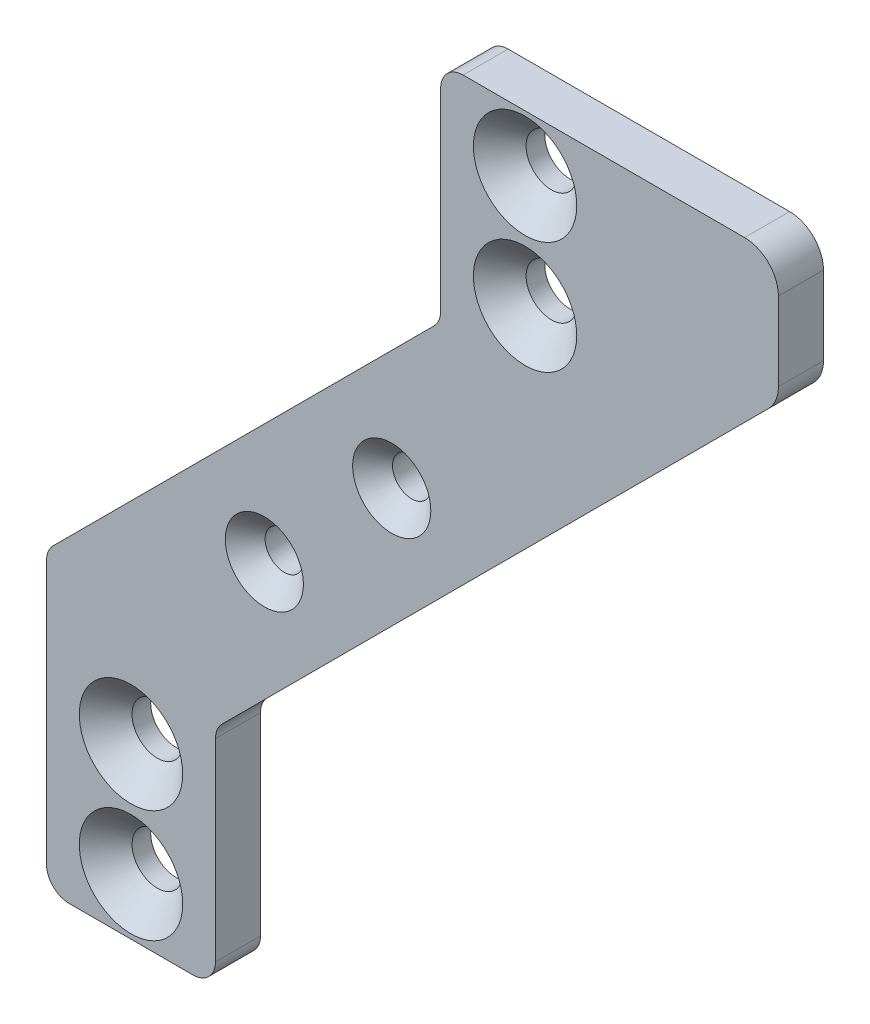
SolidWorks part; units mm, degrees
material "Thornel Mat VMA"
ref_plane "前视基准面" through (0, 0, 0) normal (0, 0, 1) x (1, 0, 0)
ref_plane "上视基准面" through (0, 0, 0) normal (0, 1, 0) x (1, 0, 0)
ref_plane "右视基准面" through (0, 0, 0) normal (1, 0, 0) x (0, 0, -1)
sketch "草图1" plane through (0, 0, 0) normal (0, 0, 1) x (1, 0, 0)
  line L0 (0, 0) -> (-15, 0)
  line L1 (-15, 0) -> (-15, 26.2132)
  line L2 (-15, 26.2132) -> (20, 61.2132)
  line L3 (20, 61.2132) -> (20, 81.2132)
  line L4 (20, 81.2132) -> (35, 81.2132)
  line L5 (35, 81.2132) -> (35, 55)
  line L6 (35, 55) -> (0, 20)
  line L7 (0, 20) -> (0, 0)
  line L8 (-95, 88.5038) -> (-95, -84.3524) construction
  line L9 (-7.5, 15) -> (-7.5, 0) construction
  line L10 (27.5, 81.2132) -> (27.5, 55.9789) construction
  circle A0 centre (-7.5, 15) radius 2 construction
  circle A1 centre (-7.5, 5) radius 2 construction
  circle A2 centre (27.5, 76.2132) radius 2 construction
  circle A3 centre (27.5, 66.2132) radius 2 construction
  point P23 (27.5, 66.2132)
  point P24 (27.5, 76.2132)
  point P25 (-7.5, 15)
  dimension "D7" = 4
  dimension "D8" = 4
  dimension "D9" = 10
  dimension "D10" = 5
  dimension "D13" = 4
  dimension "D14" = 4
  dimension "D15" = 10
  dimension "D16" = 5
  dimension "D1" = 260
  dimension "D2" = 190
  dimension "D3" = 45
  dimension "D4" = 15
  dimension "D5" = 15
  dimension "D6" = 15
  dimension "D11" = 20
  dimension "D12" = 20
extrude "凸台-拉伸1" add sketch "草图1" along normal blind 4
fillet "圆角1" radius 2 8 edges at (0, 0, 2) (-15, 0, 2) (-15, 26.2132, 2) (20, 61.2132, 2) (20, 81.2132, 2) (35, 55, 2) (0, 20, 2) (35, 81.2132, 2)
hole_wizard "M4 六角凹锥坑头螺钉的锥形沉头孔1" positions "3D草图2" profile "草图3" countersink size "M4" standard "DIN"
sketch3d "3D草图2"
  point P0 (27.5, 76.2132, 4)
  point P2 (27.5, 66.2132, 4)
  point P4 (-7.5, 15, 4)
  point P6 (-7.5, 5, 4)
sketch "草图3" plane through (27.5, 76.2132, 4) normal (1, 0, 0) x (0, -1, 0)
  line L0 (0, 0) -> (0, 25.8519)
  line L1 (0, 25.8519) -> (2.25, 24.5)
  line L2 (2.25, 24.5) -> (2.25, 2.34)
  line L3 (2.25, 2.34) -> (4.59, 0)
  line L5 (4.59, 0) -> (0, 0)
  line L6 (-2.25, 2.34) -> (-4.59, 0) construction
  line L10 (0, 25.8519) -> (-2.25, 24.5) construction
  line L11 (0, -6.35) -> (0, 107.95) construction
  dimension "孔直径" = 4.5
  dimension "孔深度" = 24.5
  dimension "近端锥形沉头孔直径" = 9.18
  dimension "近端锥形沉头孔角度" = 90
  dimension "导头角度" = 118
sketch "草图4" plane through (0, 0, 4) normal (0, 0, 1) x (1, 0, 0)
  line L0 (-4.7175, 25.8891) -> (24.7175, 55.3241) construction
  line L1 (19.4142, 60.6274) -> (-14.4142, 26.799) construction
  line L2 (0.5858, 20.5858) -> (-10.0208, 31.1924) construction
  line L3 (19.4142, 60.6274) -> (30.0208, 50.0208) construction
  line L4 (0.5858, 20.5858) -> (34.4142, 54.4142) construction
  point P4 (10, 40.6066)
  point P5 (4.3431, 34.9497)
  point P6 (24.7175, 55.3241)
  point P15 (15.6569, 46.2635)
  dimension "D2" = 8
  dimension "D1" = 8
hole_wizard "M3 六角凹锥坑头螺钉的锥形沉头孔1" positions "3D草图3" profile "草图5" countersink size "M3" standard "DIN"
sketch3d "3D草图3"
  point P0 (4.3431, 34.9497, 4)
  point P4 (15.6569, 46.2635, 4)
sketch "草图5" plane through (4.3431, 34.9497, 4) normal (1, 0, 0) x (0, -1, 0)
  line L0 (0, 0) -> (0, 25.5215)
  line L1 (0, 25.5215) -> (1.7, 24.5)
  line L2 (1.7, 24.5) -> (1.7, 1.77)
  line L3 (1.7, 1.77) -> (3.47, 0)
  line L5 (3.47, 0) -> (0, 0)
  line L6 (-1.7, 1.77) -> (-3.47, 0) construction
  line L10 (0, 25.5215) -> (-1.7, 24.5) construction
  line L11 (0, -6.35) -> (0, 107.95) construction
  dimension "孔直径" = 3.4
  dimension "孔深度" = 24.5
  dimension "近端锥形沉头孔直径" = 6.94
  dimension "近端锥形沉头孔角度" = 90
  dimension "导头角度" = 118
sketch "草图6" plane through (0, 0, 4) normal (0, 0, 1) x (1, 0, 0)
  line L0 (34.4142, 54.4142) -> (50, 70)
  line L2 (50, 70) -> (50, 81.2132)
  line L3 (50, 81.2132) -> (33, 81.2132)
  line L5 (35, 55.8284) -> (35, 79.2132) construction
  line L6 (35, 55.8284) -> (35, 79.2132)
  arc A0 (35, 79.2132) -> (33, 81.2132) centre (33, 79.2132) ccw construction
  arc A1 (34.4142, 54.4142) -> (35, 55.8284) centre (33, 55.8284) ccw construction
  arc A2 (34.4142, 54.4142) -> (35, 55.8284) centre (33, 55.8284) ccw
  arc A3 (35, 79.2132) -> (33, 81.2132) centre (33, 79.2132) ccw
  dimension "D1" = 15
  dimension "D2" = 45
extrude "凸台-拉伸2" add sketch "草图6" against normal up to surface (4 mm away) up to face at (2.6431, 34.9497, 0)
fillet "圆角2" radius 3 2 edges at (50, 70, 2) (50, 81.2132, 2)
